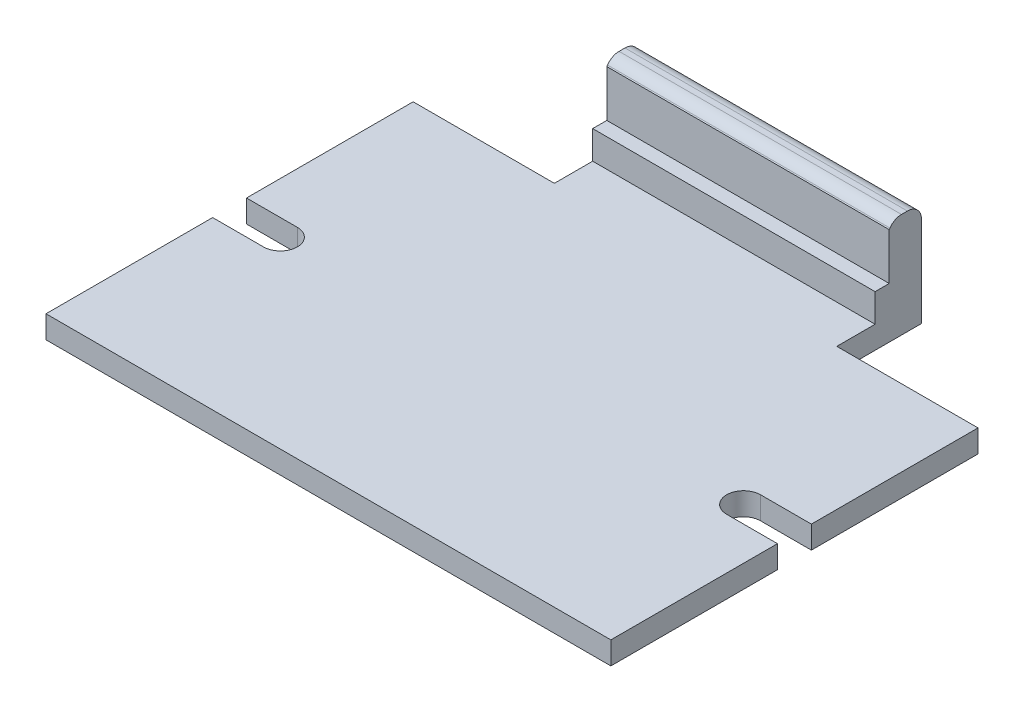
SolidWorks part; units mm, degrees
material "Сталь AISI 1020, холоднокатаная"
ref_plane "Спереди" through (0, 0, 0) normal (0, 0, 1) x (1, 0, 0)
ref_plane "Сверху" through (0, 0, 0) normal (0, 1, 0) x (1, 0, 0)
ref_plane "Справа" through (0, 0, 0) normal (1, 0, 0) x (0, 0, -1)
sketch "Эскиз1" plane through (0, 0, 0) normal (1, 0, 0) x (0, 0, -1)
  line L0 (-80.9863, 0) -> (79.0137, 0)
  line L1 (79.0137, 0) -> (79.0137, 32)
  line L2 (74.0137, 37) -> (71.9226, 37)
  line L3 (49.0137, 8) -> (-80.9863, 8)
  line L4 (-80.9863, 8) -> (-80.9863, 0)
  line L5 (67.8268, 34.8679) -> (49.0137, 8)
  arc A0 (71.9226, 37) -> (67.8268, 34.8679) centre (71.9226, 32) ccw
  arc A1 (79.0137, 32) -> (74.0137, 37) centre (74.0137, 32) ccw
  point P11 (79.0137, 37)
  dimension "D4" = 5
  dimension "D1" = 35
  dimension "D2" = 37
  dimension "D3" = 8
  dimension "D6" = 160
extrude "Бобышка-Вытянуть1" add sketch "Эскиз1" along normal blind 200
sketch "Эскиз2" plane through (0, 0, 0) normal (0, -1, 0) x (1, 0, 0)
  line L0 (200, -49.0137) -> (0, -49.0137) construction
  line L1 (50, -49.0137) -> (0, -49.0137)
  line L2 (50, -49.0137) -> (50, -79.0137)
  line L3 (50, -79.0137) -> (0, -79.0137)
  line L4 (0, -49.0137) -> (0, -79.0137)
  line L5 (100, -79.0137) -> (100, -49.0137) construction
  line L6 (200, -79.0137) -> (0, -79.0137) construction
  line L7 (200, -49.0137) -> (200, -79.0137)
  line L8 (150, -79.0137) -> (200, -79.0137)
  line L9 (150, -49.0137) -> (150, -79.0137)
  line L10 (150, -49.0137) -> (200, -49.0137)
  dimension "D1" = 50
extrude "Вырез-Вытянуть1" cut sketch "Эскиз2" against normal blind 52
sketch "Эскиз3" plane through (0, 0, 0) normal (0, -1, 0) x (1, 0, 0)
  line L0 (0, 15.9863) -> (200, 15.9863) construction
  line L1 (0, 80.9863) -> (0, -49.0137) construction
  line L2 (200, 80.9863) -> (200, -49.0137) construction
  line L3 (100, 80.9863) -> (100, -79.0137) construction
  line L4 (200, 80.9863) -> (0, 80.9863) construction
  line L5 (150, -79.0137) -> (50, -79.0137) construction
  line L6 (18, 15.9863) -> (0, 15.9863) construction
  line L7 (18, 9.9863) -> (0, 9.9863)
  line L8 (18, 21.9863) -> (0, 21.9863)
  line L9 (182, 15.9863) -> (200, 15.9863) construction
  line L10 (182, 9.9863) -> (200, 9.9863)
  line L11 (182, 21.9863) -> (200, 21.9863)
  arc A0 (18, 9.9863) -> (18, 21.9863) centre (18, 15.9863) ccw
  arc A1 (0, 21.9863) -> (0, 9.9863) centre (0, 15.9863) ccw
  arc A2 (182, 9.9863) -> (182, 21.9863) centre (182, 15.9863) cw
  arc A3 (200, 21.9863) -> (200, 9.9863) centre (200, 15.9863) cw
  point P13 (9, 15.9863)
  point P19 (191, 15.9863)
  dimension "D1" = 12
  dimension "D2" = 18
extrude "Вырез-Вытянуть2" cut sketch "Эскиз3" against normal blind 10
sketch "Эскиз4" plane through (150, 0, 0) normal (1, 0, 0) x (0, 0, -1)
  line L0 (67.5773, 37) -> (67.5773, 18)
  line L1 (67.5773, 18) -> (62.5773, 18)
  line L2 (62.5773, 18) -> (62.5773, 8)
  line L3 (72.9682, 37) -> (67.5773, 37) construction
  line L4 (71.9226, 37) -> (74.0137, 37) construction
  line L5 (49.0137, 0) -> (79.0137, 0) construction
  line L6 (49.0137, 8) -> (79.0137, 8) construction
  line L7 (79.0137, 32) -> (79.0137, 0) construction
  line L8 (62.5773, 8) -> (49.0137, 8)
  line L9 (49.0137, 8) -> (49.0137, 37)
  line L10 (49.0137, 37) -> (67.5773, 37)
  dimension "D1" = 5
  dimension "D2" = 18
extrude "Вырез-Вытянуть4" cut sketch "Эскиз4" against normal blind 105.1987
